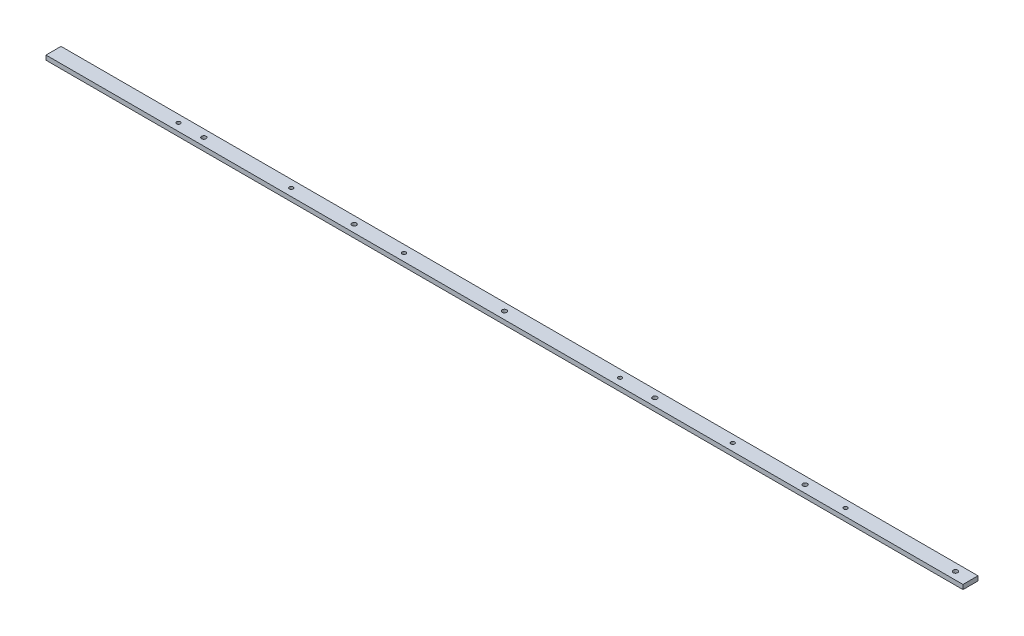
SolidWorks part; units mm, degrees
ref_plane "Front" through (0, 0, 0) normal (0, 0, 1) x (1, 0, 0)
ref_plane "Top" through (0, 0, 0) normal (0, 1, 0) x (1, 0, 0)
ref_plane "Right" through (0, 0, 0) normal (1, 0, 0) x (0, 0, -1)
sketch "Sketch1" plane through (0, 0, 0) normal (1, 0, 0) x (0, 0, -1)
  line L1 (-10, 0) -> (10, 0)
  line L2 (-10, 0) -> (-10, 6)
  line L3 (-10, 6) -> (10, 6)
  line L4 (10, 0) -> (10, 6)
  dimension "D1" = 6
  dimension "D2" = 20
extrude "Boss-Extrude1" add sketch "Sketch1" along normal blind 1220
sketch "Sketch2" plane through (0, 6, 0) normal (0, 1, 0) x (1, 0, 0)
  circle A0 centre (200, 0) radius 3
  circle A1 centre (400, 0) radius 3
  circle A2 centre (600, 0) radius 3
  circle A3 centre (800, 0) radius 3
  circle A4 centre (1000, 0) radius 3
  circle A5 centre (1200, 0) radius 3
  dimension "D1" = 6
  dimension "D2" = 200
  dimension "D4" = 200
  dimension "D3" = 6
extrude "Cut-Extrude1" cut sketch "Sketch2" against normal through all
hole_wizard "M6 Tapped Hole1" positions "Sketch3" profile "Sketch4" tap size "M6" standard "ISO" end condition through all
sketch "Sketch3" plane through (0, 6, 0) normal (0, 1, 0) x (1, 0, 0)
  line L0 (45, 10) -> (45, -10) construction
  line L1 (1220, 10) -> (0, 10) construction
  line L2 (1220, -10) -> (0, -10) construction
  line L4 (1175, 10) -> (1175, -10) construction
  line L6 (587.5, 10) -> (587.5, -10) construction
  line L7 (587.5, -10) -> (632.5, -10) construction
  line L8 (632.5, -10) -> (632.5, 10) construction
  line L9 (632.5, 10) -> (587.5, 10) construction
  line L11 (610, -10) -> (610, 10) construction
  line L13 (1220, 10) -> (1220, -10) construction
  line L14 (22.5, 10) -> (22.5, -10) construction
  line L16 (1197.5, 10) -> (1197.5, -10) construction
  line L18 (166.25, 0) -> (316.25, 0) construction
  line L19 (316.25, 0) -> (466.25, 0) construction
  line L22 (903.75, 0) -> (753.75, 0) construction
  line L23 (1053.75, 0) -> (903.75, 0) construction
  point P35 (166.25, 0)
  point P37 (316.25, 0)
  point P39 (466.25, 0)
  point P55 (753.75, 0)
  point P56 (903.75, 0)
  point P57 (1053.75, 0)
  dimension "D1" = 45
  dimension "D2" = 610
  dimension "D3" = 45
  dimension "D4" = 45
  dimension "D5" = 22.5
  dimension "D6" = 22.5
  dimension "D7" = 150
  dimension "D8" = 293.75
sketch "Sketch4" plane through (1053.75, 6, 0) normal (1, 0, 0) x (0, 0, 1)
  line L0 (0, 0) -> (0, 6)
  line L1 (0, 6) -> (2.5, 6)
  line L2 (2.5, 6) -> (2.5, 0)
  line L5 (2.5, 0) -> (0, 0)
  line L11 (0, -6.35) -> (0, 107.95) construction
  dimension "Thru Tap Drill Dia." = 5
  dimension "Thru Tap Drill Depth" = 6
cosmetic thread "Hole Thread1" parameters "D2"=6
cosmetic thread "Hole Thread2" parameters "D2"=6
cosmetic thread "Hole Thread3" parameters "D2"=6
cosmetic thread "Hole Thread4" parameters "D2"=6
cosmetic thread "Hole Thread5" parameters "D2"=6
cosmetic thread "Hole Thread6" parameters "D2"=6
